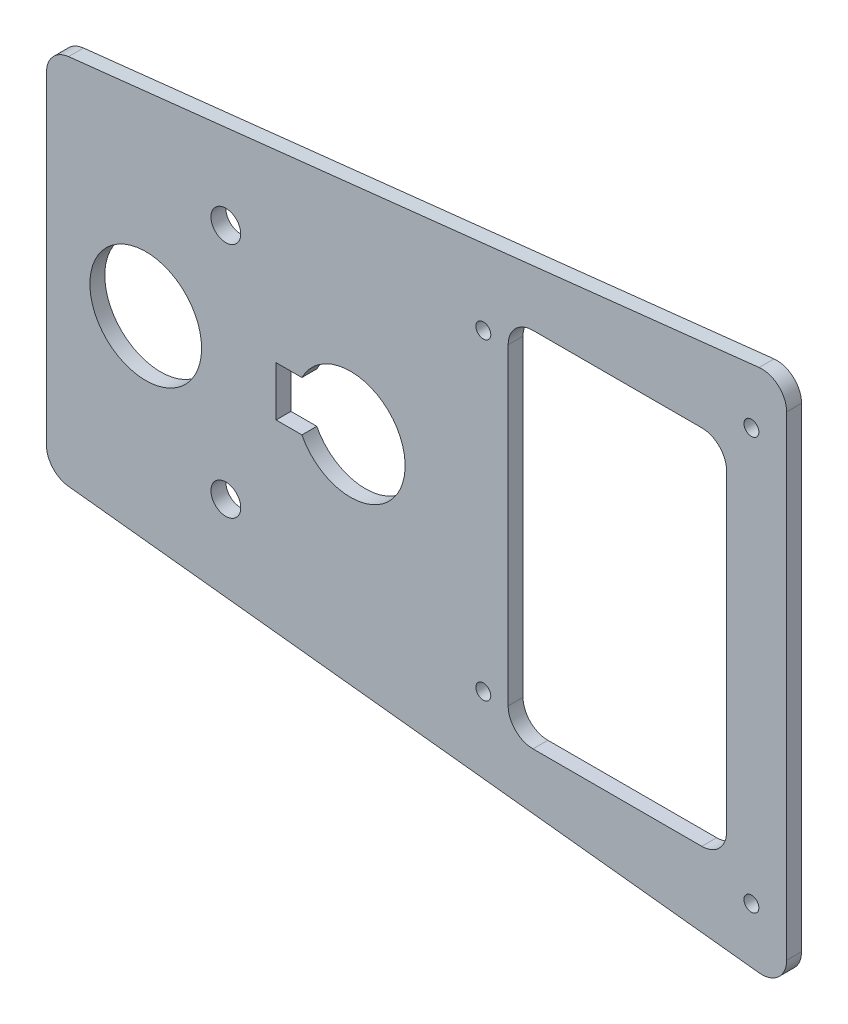
SolidWorks part; units mm, degrees
ref_plane "Front Plane" through (0, 0, 0) normal (1, 0, 0) x (0, 1, 0)
ref_plane "Top Plane" through (0, 0, 0) normal (0, 0, 1) x (0, 1, 0)
ref_plane "Right Plane" through (0, 0, 0) normal (0, 1, 0) x (-1, 0, 0)
sketch "Sketch1" plane through (0, 0, 0) normal (0, 0, 1) x (0, 1, 0)
  line L0 (53.415, 0) -> (-53.415, 0)
  line L1 (-53.415, 0) -> (-37, 149.0991)
  line L2 (-37, 149.0991) -> (37, 149.0991)
  line L3 (37, 149.0991) -> (53.415, 0)
  point P4 (0, 0)
  dimension "D1" = 106.83
  dimension "D2" = 150
  dimension "D3" = 74
extrude "Boss-Extrude1" add sketch "Sketch1" along normal mid plane 3
fillet "Fillet1" radius 5 4 edges at (-149.0991, -37, 0) (-149.0991, 37, 0) (0, 53.415, 0) (0, -53.415, 0)
sketch "Sketch2" plane through (0, 0, 1.5) normal (0, 0, 1) x (1, 0, 0)
  line L0 (0, 0) -> (-149.0991, 0) construction
  line L1 (-149.0991, 32.5203) -> (-149.0991, -32.5203) construction
  line L2 (-149.0991, 0) -> (-129.0991, 0)
  line L3 (-129.0991, 0) -> (-97.0991, 0)
  line L4 (-97.0991, 0) -> (-34.0991, 0)
  line L5 (-56.0991, 36.5) -> (-12.0991, 36.5)
  line L6 (-61.0991, -41.5) -> (-7.0991, -41.5) construction
  line L7 (-61.0991, -41.5) -> (-61.0991, 41.5) construction
  line L8 (-61.0991, 41.5) -> (-7.0991, 41.5) construction
  line L9 (-7.0991, -41.5) -> (-7.0991, 41.5) construction
  line L10 (-61.0991, -41.5) -> (-7.0991, 41.5) construction
  line L11 (-61.0991, 41.5) -> (-7.0991, -41.5) construction
  line L12 (-12.0991, -36.5) -> (-12.0991, 36.5)
  line L13 (-56.0991, -36.5) -> (-12.0991, -36.5)
  line L14 (-56.0991, -36.5) -> (-56.0991, 36.5)
  line L15 (-117.8491, 0) -> (-56.0991, 0) construction
  line L16 (-98.8491, 0) -> (-102.8491, 0) construction
  line L17 (-102.8491, -5) -> (-102.8491, 5)
  line L18 (-102.8491, 5) -> (-97.6471, 5)
  line L19 (-102.8491, -5) -> (-97.6471, -5)
  line L20 (-61.0991, -41.5) -> (-61.0991, -31.5)
  circle A0 centre (-129.0991, 0) radius 11.25
  circle A2 centre (-61.0991, 41.5) radius 1.5 construction
  circle A3 centre (-7.0991, 41.5) radius 1.5
  circle A4 centre (-61.0991, -41.5) radius 1.5 construction
  circle A5 centre (-7.0991, -41.5) radius 1.5
  arc A6 (-97.6471, -5) -> (-97.6471, 5) centre (-87.8491, 0) ccw
  arc A7 (-97.6471, 5) -> (-98.8491, 0) centre (-87.8491, 0) ccw construction
  arc A8 (-98.8491, 0) -> (-97.6471, -5) centre (-87.8491, 0) ccw construction
  circle A9 centre (-61.0991, -31.5) radius 1.5
  circle A10 centre (-61.0991, 31.5) radius 1.5
  point P28 (-92.0743, 0)
  point P31 (-102.8491, 0)
  dimension "D4" = 22.5
  dimension "D5" = 22
  dimension "D8" = 3
  dimension "D10" = 30
  dimension "D13" = 10
  dimension "D1" = 20
  dimension "D2" = 32
  dimension "D3" = 63
  dimension "D6" = 54
  dimension "D7" = 83
  dimension "D9" = 5
  dimension "D11" = 4
  dimension "D12" = 10
extrude "Cut-Extrude1" cut sketch "Sketch2" against normal blind 3
fillet "Fillet2" radius 5 4 edges at (-12.0991, 36.5, 0) (-12.0991, -36.5, 0) (-56.0991, -36.5, 0) (-56.0991, 36.5, 0)
sketch "Sketch3" plane through (0, 0, 1.5) normal (0, 0, 1) x (1, 0, 0)
  line L0 (-144.6463, -37.4902) -> (-5.5472, -52.8043) construction
  line L1 (-5.5472, 52.8043) -> (-144.6463, 37.4902) construction
  line L6 (-5.5472, 52.8043) -> (-144.6463, 37.4902) construction
  line L7 (-144.6463, -37.4902) -> (-5.5472, -52.8043) construction
  line L8 (-5, 47.8343) -> (-144.0991, 32.5203) construction
  line L9 (-144.0991, -32.5203) -> (-5, -47.8343) construction
  line L10 (-144.0991, -32.5203) -> (-114.2793, -35.8033)
  line L11 (-114.2793, -35.8033) -> (-112.9661, -23.8753)
  line L12 (-77.8491, 0) -> (-50077.8491, 0) construction
  circle A0 centre (-112.9661, -23.8753) radius 3
  arc A1 (-97.6471, -5) -> (-97.6471, 5) centre (-87.8491, 0) ccw construction
  circle A2 centre (-112.9661, 23.8753) radius 3
  point P16 (-76.8491, 0)
  dimension "D3" = 6
  dimension "D1" = 5
  dimension "D2" = 5
  dimension "D4" = 12
  dimension "D5" = 30
extrude "Cut-Extrude2" cut sketch "Sketch3" against normal up to next contours A2 | A0
